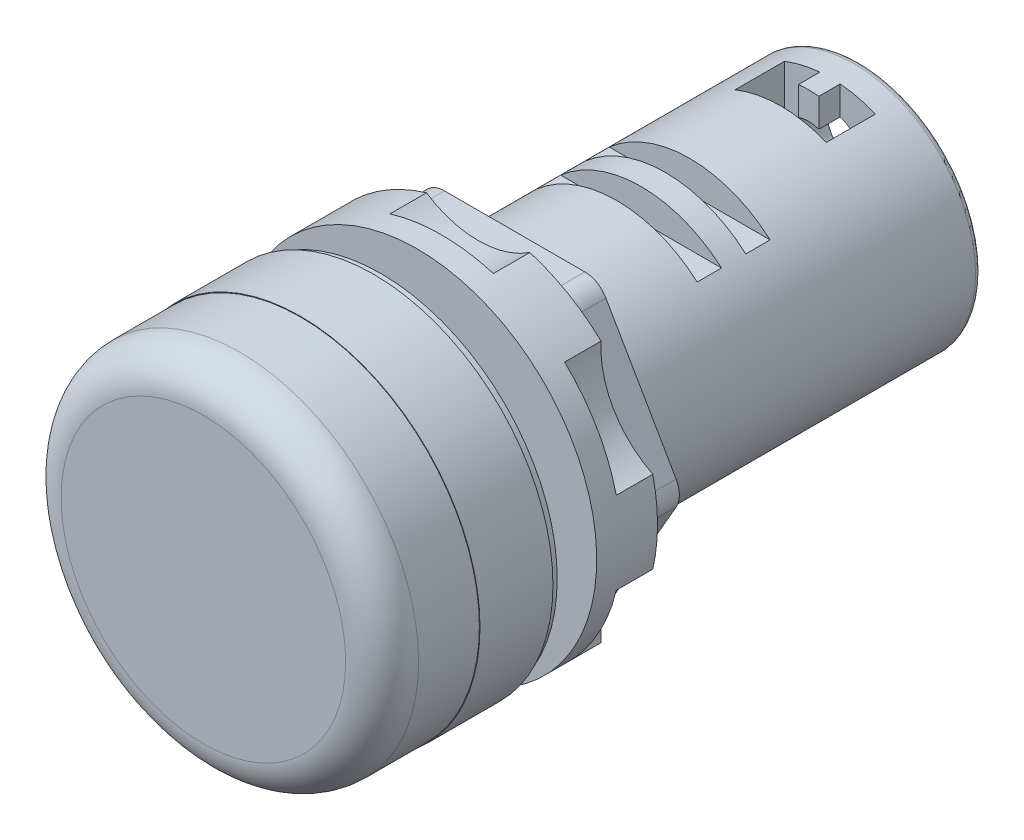
SolidWorks part; units mm, degrees
ref_plane "Frontal" through (0, 0, 0) normal (0, 0, 1) x (1, 0, 0)
ref_plane "Superior" through (0, 0, 0) normal (0, 1, 0) x (1, 0, 0)
ref_plane "Direito" through (0, 0, 0) normal (1, 0, 0) x (0, 0, -1)
sketch "Esboço1" plane through (0, 0, 0) normal (0, 0, 1) x (1, 0, 0)
  circle A0 centre (0, 0) radius 14.75
  dimension "D1" = 29.5
extrude "Extrusão1" add sketch "Esboço1" along normal blind 6
sketch "Esboço2" plane through (0, 0, 0) normal (0, 0, -1) x (-1, 0, 0)
  circle A0 centre (0, 0) radius 10
  dimension "D1" = 20
extrude "Extrusão2" add sketch "Esboço2" along normal blind 40
sketch "Esboço3" plane through (0, 0, 6) normal (0, 0, 1) x (1, 0, 0)
  circle A0 centre (0, 0) radius 11
  dimension "D1" = 22
extrude "Extrusão3" add sketch "Esboço3" along normal blind 5
sketch "Esboço4" plane through (0, 0, 6) normal (0, 0, 1) x (1, 0, 0)
  circle A0 centre (0, 0) radius 14.7
  circle A1 centre (0, 0) radius 12.5
  dimension "D1" = 29.4
  dimension "D2" = 25
extrude "Extrusão4" add sketch "Esboço4" along normal blind 8
sketch "Esboço5" plane through (0, 0, 14) normal (0, 0, 1) x (1, 0, 0)
  circle A0 centre (0, 0) radius 14.7
extrude "Extrusão5" add sketch "Esboço5" against normal blind 2
fillet "Filete2" radius 3 1 edges at (14.7, 0, 14)
sketch "Esboço6" plane through (0, 0, 0) normal (0, 0, -1) x (-1, 0, 0)
  circle A0 centre (0, 0) radius 14.5
  dimension "D1" = 29
extrude "Extrusão6" add sketch "Esboço6" along normal blind 0.6
sketch "Esboço7" plane through (0, 0, -0.6) normal (0, 0, -1) x (-1, 0, 0)
  circle A0 centre (0, 0) radius 14.75
  dimension "D1" = 29.5
extrude "Extrusão7" add sketch "Esboço7" along normal blind 5 from offset 3
sketch "Esboço8" plane through (0, 0, -8.6) normal (0, 0, -1) x (-1, 0, 0)
  line L0 (-4.25, 14.1244) -> (4.25, 14.1244) construction
  circle A0 centre (0, 0) radius 14.75 construction
  arc A1 (-4.25, 14.1244) -> (4.25, 14.1244) centre (0, 20.5353) ccw
  arc A2 (-4.25, 14.1244) -> (4.25, 14.1244) centre (0, 9.8744) cw
  dimension "D1" = 8.5
extrude "Corte-extrusão1" cut sketch "Esboço8" against normal blind 3
pattern_circular "CirPattern1" count 6 over 360 about axis through (0, 0, 0) along (0, 0, 1) of "Corte-extrusão1"
sketch "Esboço9" plane through (0, 0, -8.6) normal (0, 0, -1) x (-1, 0, 0)
  line L1 (-7.5056, 11) -> (-13.2791, 1)
  line L2 (-13.2791, -1) -> (-7.5056, -11)
  line L3 (-5.7735, -12) -> (5.7735, -12)
  line L4 (7.5056, -11) -> (13.2791, -1)
  line L5 (13.2791, 1) -> (7.5056, 11)
  line L6 (5.7735, 12) -> (-5.7735, 12)
  circle A0 centre (0, 0) radius 12 construction
  arc A1 (-7.5056, 11) -> (-5.7735, 12) centre (-5.7735, 10) cw
  arc A2 (-13.2791, 1) -> (-13.2791, -1) centre (-11.547, 0) ccw
  arc A3 (-7.5056, -11) -> (-5.7735, -12) centre (-5.7735, -10) ccw
  arc A4 (5.7735, -12) -> (7.5056, -11) centre (5.7735, -10) ccw
  arc A5 (13.2791, -1) -> (13.2791, 1) centre (11.547, 0) ccw
  arc A6 (7.5056, 11) -> (5.7735, 12) centre (5.7735, 10) ccw
  dimension "D2" = 2
  dimension "D1" = 24
extrude "Extrusão8" add sketch "Esboço9" along normal blind 3
fillet "Filete3" radius 0.5 1 edges at (-10, 0, -40)
sketch "Esboço10" plane through (0, 0, -40) normal (0, 0, -1) x (-1, 0, 0)
  line L0 (-20, 12.5) -> (20, 12.5)
  line L1 (-15, 7.5) -> (15, 7.5)
  line L2 (-15, 7.5) -> (-15, -7.5)
  line L3 (-15, -7.5) -> (15, -7.5)
  line L4 (15, 7.5) -> (15, -7.5)
  line L5 (20, 12.5) -> (20, -12.5)
  line L6 (-20, -12.5) -> (20, -12.5)
  line L7 (-20, 12.5) -> (-20, -12.5)
  dimension "D1" = 15
  dimension "D2" = 7.5
  dimension "D3" = 30
  dimension "D4" = 15
  dimension "D5" = 5
extrude "Corte-extrusão2" cut sketch "Esboço10" against normal blind 2 from offset 14 offset against normal yes
pattern_linear "LPattern1" count 2 spacing 4 along (0, 0, 1) of "Corte-extrusão2"
sketch "Esboço11" plane through (0, 0, -40) normal (0, 0, -1) x (-1, 0, 0)
  line L0 (0, 0) -> (-3.6369, 0) construction
  circle A0 centre (0, 5) radius 2.75
  circle A1 centre (0, -5) radius 2.75
  dimension "D1" = 5.5
  dimension "D2" = 5
extrude "Corte-extrusão3" cut sketch "Esboço11" against normal blind 5
sketch3d "3DSketch2"
  line L0 (0, 0, -40.0073) -> (0, 0, -31.3042) construction
  line L1 (-3.75, 0, -37.5271) -> (-0.8278, 0, -37.5271)
  line L2 (-3.75, 0, -37.5271) -> (-3.75, 0, -33.48)
  line L3 (-3.75, 0, -33.48) -> (3.75, 0, -33.48)
  line L4 (3.75, 0, -37.5271) -> (3.75, 0, -33.48)
  line L5 (0.8482, 0, -37.5271) -> (3.75, 0, -37.5271)
  line L7 (-0.8278, 0, -37.5271) -> (-0.8278, 0, -35.7734)
  line L8 (-0.8278, 0, -35.7734) -> (0.8482, 0, -35.7734)
  line L9 (0.8482, 0, -37.5271) -> (0.8482, 0, -35.7734)
  dimension "D1" = 7.5
  dimension "D2" = 3.75
extrude "Corte-extrusão4" cut sketch "3DSketch2" along direction (0, 1, 0) on the side against the normal mid plane 25
